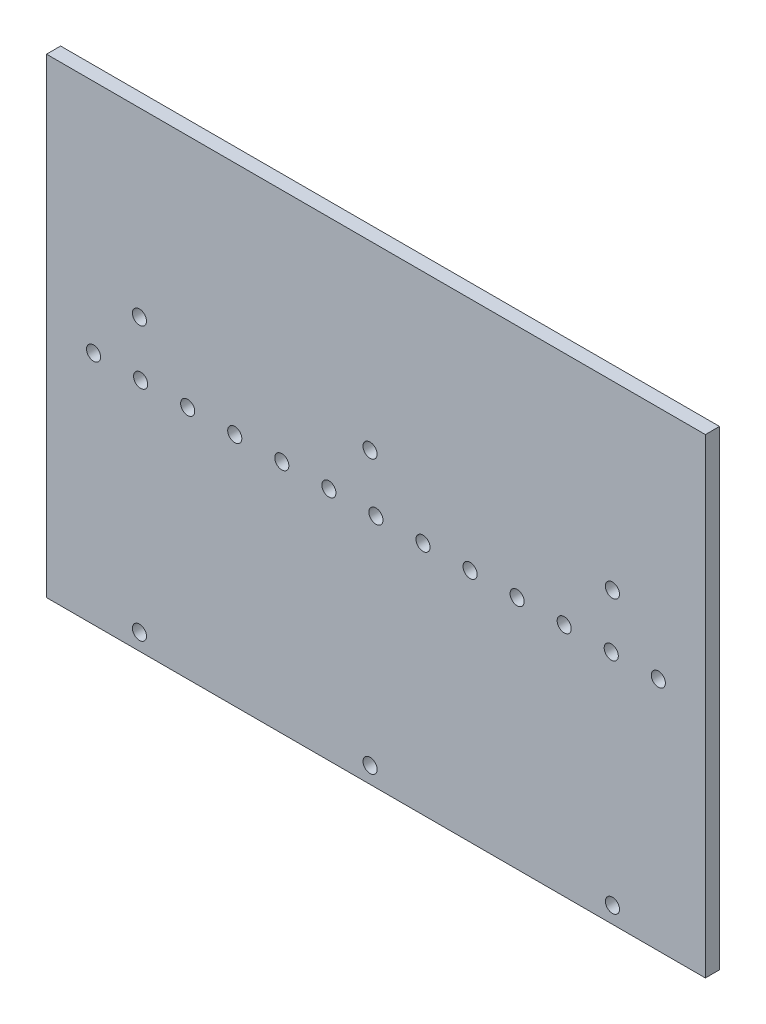
SolidWorks part; units mm, degrees
ref_plane "Front Plane" through (0, 0, 0) normal (0, 0, 1) x (1, 0, 0)
ref_plane "Top Plane" through (0, 0, 0) normal (0, 1, 0) x (1, 0, 0)
ref_plane "Right Plane" through (0, 0, 0) normal (1, 0, 0) x (0, 0, -1)
sketch "Sketch1" plane through (0, 0, 0) normal (0, 0, 1) x (1, 0, 0)
  line L1 (-70, 50) -> (70, 50)
  line L2 (-70, 50) -> (-70, -50)
  line L3 (-70, -50) -> (70, -50)
  line L4 (70, 50) -> (70, -50)
  line L5 (-70, 50) -> (70, -50) construction
  line L6 (-70, -50) -> (70, 50) construction
  point P0 (0, 0)
  dimension "D1" = 140
  dimension "D2" = 100
extrude "Boss-Extrude1" add sketch "Sketch1" along normal blind 3
sketch "Sketch2" plane through (0, 0, 3) normal (0, 0, 1) x (1, 0, 0)
  line L0 (-70, 0) -> (70, 0) construction
  line L16 (-70, 50) -> (-70, -50) construction
  circle A29 centre (0, 0) radius 1.5
  circle A30 centre (10, 0) radius 1.5
  circle A31 centre (20, 0) radius 1.5
  circle A32 centre (30, 0) radius 1.5
  circle A33 centre (40, 0) radius 1.5
  circle A34 centre (50, 0) radius 1.5
  circle A35 centre (60, 0) radius 1.5
  circle A36 centre (-10, 0) radius 1.5
  circle A37 centre (-20, 0) radius 1.5
  circle A38 centre (-30, 0) radius 1.5
  circle A39 centre (-40, 0) radius 1.5
  circle A40 centre (-50, 0) radius 1.5
  circle A41 centre (-60, 0) radius 1.5
  dimension "D1" = 3
  dimension "D2" = 7
extrude "Cut-Extrude1" cut sketch "Sketch2" against normal blind 4
sketch "Sketch3" plane through (0, 0, 3) normal (0, 0, 1) x (1, 0, 0)
  line L3 (70, -50) -> (70, -46.5) construction
  line L10 (70, -50) -> (70, 50) construction
  circle A0 centre (50.25, -46.5) radius 1.5
  circle A1 centre (-50.25, -46.5) radius 1.5
  circle A3 centre (-1.25, -46.5) radius 1.5
  circle A5 centre (-1.25, 11.5) radius 1.5
  circle A6 centre (50.25, 11.5) radius 1.5
  circle A7 centre (-50.25, 11.5) radius 1.5
  point P6 (0, 0)
  dimension "D3" = 3
  dimension "D6" = 3
  dimension "D7" = 3
  dimension "D8" = 3
  dimension "D9" = 3
  dimension "D10" = 3
  dimension "D1" = 100.5
  dimension "D2" = 3.5
  dimension "D4" = 58
  dimension "D5" = 51.5
  dimension "D11" = 49
extrude "Cut-Extrude2" cut sketch "Sketch3" against normal blind 10
